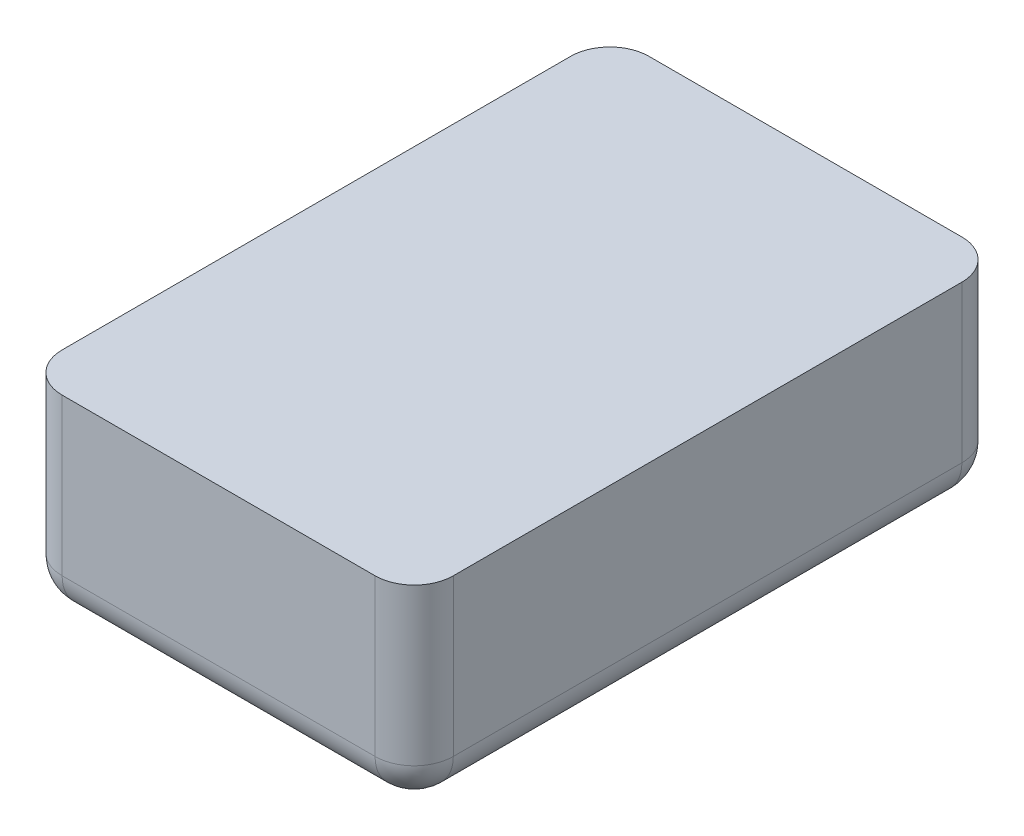
SolidWorks part; units mm, degrees
ref_plane "Front Plane" through (0, 0, 0) normal (0, 0, 1) x (1, 0, 0)
ref_plane "Top Plane" through (0, 0, 0) normal (0, 1, 0) x (1, 0, 0)
ref_plane "Right Plane" through (0, 0, 0) normal (1, 0, 0) x (0, 0, -1)
sketch "Sketch1" plane through (0, 0, 0) normal (0, 1, 0) x (1, 0, 0)
  line L1 (0, 0) -> (100, 0)
  line L2 (0, 0) -> (0, 150)
  line L3 (0, 150) -> (100, 150)
  line L4 (100, 0) -> (100, 150)
  dimension "D1" = 150
  dimension "D2" = 100
extrude "Boss-Extrude1" add sketch "Sketch1" along normal blind 50
fillet "Fillet1" radius 10 8 edges at (50, 0, -150) (100, 0, -75) (50, 0, 0) (0, 0, -75) (0, 25, 0) (100, 25, 0) (100, 25, -150) (0, 25, -150)
sketch "Sketch2" plane through (0, 50, 0) normal (0, 1, 0) x (1, 0, 0)
  line L0 (50, 150) -> (50, 0) construction
  line L1 (90, 150) -> (10, 150) construction
  line L2 (10, 0) -> (90, 0) construction
  line L3 (100, 75) -> (0, 75) construction
  line L4 (0, 140) -> (0, 10) construction
  point P11 (50, 75)
